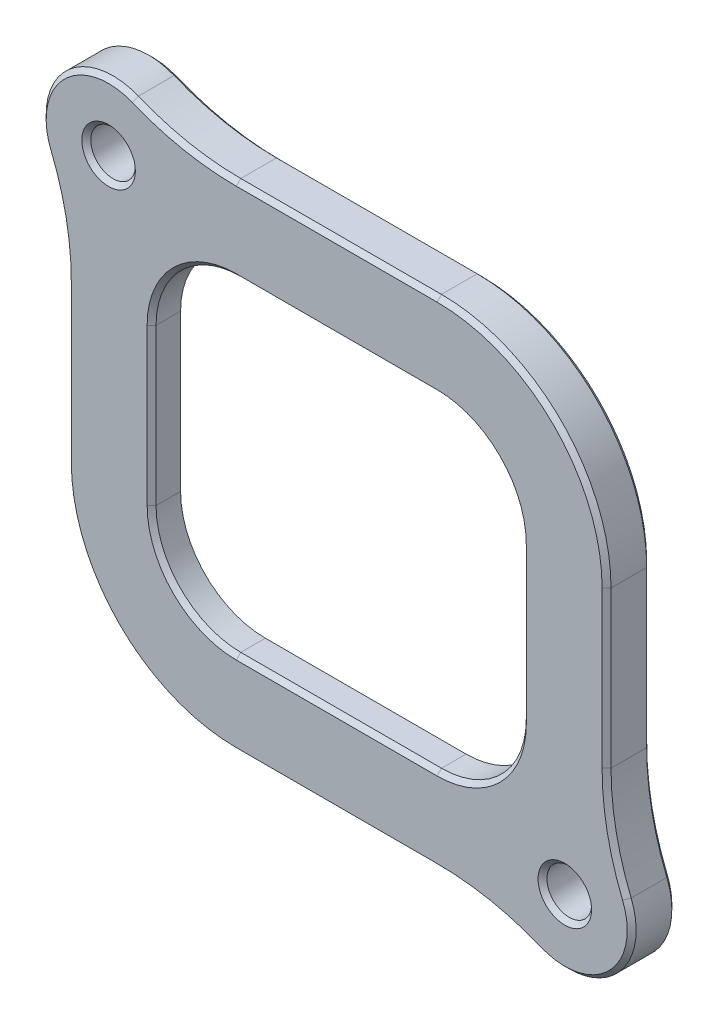
SolidWorks part; units mm, degrees
ref_plane "Ebene vorne" through (0, 0, 0) normal (1, 0, 0) x (0, 1, 0)
ref_plane "Ebene oben" through (0, 0, 0) normal (0, 0, 1) x (0, 1, 0)
ref_plane "Ebene rechts" through (0, 0, 0) normal (0, 1, 0) x (-1, 0, 0)
sketch "Skizze1" plane through (0, 0, 0) normal (0, 0, 1) x (0, 1, 0)
  line L0 (-3.5, 12.1) -> (3.5, 12.1)
  line L1 (-3.5, 9.5) -> (3.5, 9.5) construction
  line L2 (-8.5, 4.5) -> (-8.5, -4.5) construction
  line L3 (-3.5, -9.5) -> (3.5, -9.5) construction
  line L4 (8.5, 4.5) -> (8.5, -4.5) construction
  line L5 (-8.5, 9.5) -> (8.5, -9.5) construction
  line L6 (-8.5, -9.5) -> (8.5, 9.5) construction
  line L7 (11.1, 4.5) -> (11.1, -4.5)
  line L8 (-3.5, -12.1) -> (3.5, -12.1)
  line L9 (-11.1, 4.5) -> (-11.1, -4.5)
  line L10 (-3.5, 8.3) -> (3.5, 8.3)
  line L11 (7.3, 4.5) -> (7.3, -4.5)
  line L12 (-3.5, -8.3) -> (3.5, -8.3)
  line L13 (-7.3, 4.5) -> (-7.3, -4.5)
  line L14 (9.2276, 10.2276) -> (3.5, 4.5) construction
  line L15 (3.5, 4.5) -> (3.5, 12.1) construction
  line L16 (-3.5, -4.5) -> (-9.2276, -10.2276) construction
  line L17 (-3.5, -4.5) -> (-3.5, -12.1) construction
  line L18 (-3.5, 9.6) -> (3.5, 9.6) construction
  line L19 (8.6, 4.5) -> (8.6, -4.5) construction
  line L20 (-3.5, -9.6) -> (3.5, -9.6) construction
  line L21 (-8.6, 4.5) -> (-8.6, -4.5) construction
  line L22 (23.2106, 4.5) -> (11.1, 4.5) construction
  arc A0 (-3.5, 9.5) -> (-8.5, 4.5) centre (-3.5, 4.5) ccw construction
  arc A1 (-8.5, -4.5) -> (-3.5, -9.5) centre (-3.5, -4.5) ccw construction
  arc A2 (3.5, -9.5) -> (8.5, -4.5) centre (3.5, -4.5) ccw construction
  arc A3 (8.5, 4.5) -> (3.5, 9.5) centre (3.5, 4.5) ccw construction
  arc A5 (3.5, -12.1) -> (11.1, -4.5) centre (3.5, -4.5) ccw
  arc A7 (-3.5, 12.1) -> (-11.1, 4.5) centre (-3.5, 4.5) ccw
  arc A8 (7.3, 4.5) -> (3.5, 8.3) centre (3.5, 4.5) ccw
  arc A9 (3.5, -8.3) -> (7.3, -4.5) centre (3.5, -4.5) ccw
  arc A10 (-7.3, -4.5) -> (-3.5, -8.3) centre (-3.5, -4.5) ccw
  arc A11 (-3.5, 8.3) -> (-7.3, 4.5) centre (-3.5, 4.5) ccw
  arc A12 (7.1062, 8.1062) -> (7.185, 8.0303) centre (9.2276, 10.2276) ccw
  arc A13 (-12.0037, -9.0904) -> (-8.0904, -13.0037) centre (-9.2276, -10.2276) ccw
  arc A14 (8.6, 4.5) -> (3.5, 9.6) centre (3.5, 4.5) ccw construction
  arc A15 (3.5, -9.6) -> (8.6, -4.5) centre (3.5, -4.5) ccw construction
  arc A16 (-8.6, -4.5) -> (-3.5, -9.6) centre (-3.5, -4.5) ccw construction
  arc A17 (-3.5, 9.6) -> (-8.6, 4.5) centre (-3.5, 4.5) ccw construction
  arc A18 (12.0037, 9.0904) -> (11.1, 4.5) centre (23.2106, 4.5) ccw
  arc A19 (3.5, 12.1) -> (8.0904, 13.0037) centre (3.5, 24.2106) ccw
  arc A20 (-12.0037, -9.0904) -> (-11.1, -4.5) centre (-23.2106, -4.5) ccw
  arc A21 (-3.5, -12.1) -> (-8.0904, -13.0037) centre (-3.5, -24.2106) ccw
  arc A22 (12.0037, 9.0904) -> (8.0904, 13.0037) centre (9.2276, 10.2276) ccw
  arc A23 (11.1, 4.5) -> (3.5, 12.1) centre (3.5, 4.5) ccw construction
  arc A24 (-7.1062, -8.1062) -> (-7.185, -8.0303) centre (-9.2276, -10.2276) ccw
  arc A25 (-11.1, -4.5) -> (-3.5, -12.1) centre (-3.5, -4.5) ccw construction
  point P0 (0, 0)
  dimension "D3" = 5
  dimension "D8" = 6
  dimension "D1" = 17
  dimension "D2" = 19
  dimension "D6" = 45
  dimension "D7" = 45
  dimension "D4" = 2.6
  dimension "D5" = 1.2
  dimension "D9" = 0.1
extrude "Aufsatz-Linear austragen1" add sketch "Skizze1" along normal blind 2
hole_wizard "Ø2.0 (2) Durchmesser Bohrung1" positions "Skizze4" profile "Skizze3" hole size "Ø2.0" standard "DIN"
sketch "Skizze4" plane through (0, 0, 2) normal (0, 0, 1) x (0, -1, 0)
  arc A0 (-12.0037, -9.0904) -> (-8.0904, -13.0037) centre (-9.2276, -10.2276) ccw construction
  arc A1 (12.0037, 9.0904) -> (8.0904, 13.0037) centre (9.2276, 10.2276) ccw construction
  point P0 (-9.2276, -10.2276)
  point P3 (9.2276, 10.2276)
  point P7 (0, 0)
  point P11 (0, 0)
sketch "Skizze3" plane through (-10.2276, 9.2276, 2) normal (1, 0, 0) x (0, -1, 0)
  line L0 (0, 0) -> (0, 2.6009)
  line L1 (0, 2.6009) -> (1, 2)
  line L2 (1, 2) -> (1, 0)
  line L5 (1, 0) -> (0, 0)
  line L10 (0, 2.6009) -> (-1, 2) construction
  line L11 (0, -6.35) -> (0, 107.95) construction
  dimension "Bohrerdurchmesser" = 2
  dimension "Bohrungstiefe" = 2
  dimension "Spitzenwinkel" = 118
sketch "Skizze5" plane through (0, 0, 0) normal (0, 0, -1) x (1, 0, 0)
  line L1 (4.5, -8.6) -> (-4.5, -8.6)
  line L2 (9.6, -3.5) -> (9.6, 3.5)
  line L3 (4.5, 8.6) -> (-4.5, 8.6)
  line L4 (-9.6, -3.5) -> (-9.6, 3.5)
  line L5 (9.6, -8.6) -> (-9.6, 8.6) construction
  line L6 (9.6, 8.6) -> (-9.6, -8.6) construction
  arc A0 (-9.6, -3.5) -> (-4.5, -8.6) centre (-4.5, -3.5) ccw
  arc A1 (4.5, -8.6) -> (9.6, -3.5) centre (4.5, -3.5) ccw
  arc A2 (9.6, 3.5) -> (4.5, 8.6) centre (4.5, 3.5) ccw
  arc A3 (-4.5, 8.6) -> (-9.6, 3.5) centre (-4.5, 3.5) ccw
  point P0 (0, 0)
  dimension "D3" = 5.1
  dimension "D1" = 19.2
  dimension "D2" = 17.2
extrude "Schnitt-Linear austragen1" cut sketch "Skizze5" against normal blind 0.7
chamfer "Fase2" distance 0.2 angle 45 44 edges at (-12.3489, 11.3489, 0) (-12.3281, 5.8393, 0) (-12.1, 0, 0) (-9.874, -8.874, 0) (0, -11.1, 0) (6.8393, -11.3281, 0) (12.3489, -11.3489, 0) (12.3281, -5.8393, 0) (12.1, 0, 0) (9.874, 8.874, 0) (0, 11.1, 0) (-6.8393, 11.3281, 0) (0, 11.1, 2) (9.874, 8.874, 2) (12.1, 0, 2) (12.3281, -5.8393, 2) (12.3489, -11.3489, 2) (6.8393, -11.3281, 2) (0, -11.1, 2) (-9.874, -8.874, 2) (-12.1, 0, 2) (-12.3281, 5.8393, 2) (-12.3489, 11.3489, 2) (-6.8393, 11.3281, 2) (0, -7.3, 2) (7.187, -6.187, 2) (8.3, 0, 2) (7.187, 6.187, 2) (0, 7.3, 2) (-7.187, 6.187, 2) (-8.3, 0, 2) (-7.187, -6.187, 2) (11.2276, -9.2276, 2) (-9.2276, 9.2276, 2) (11.2276, -9.2276, 0) (-9.2276, 9.2276, 0) (8.1062, 7.1062, 0) (9.6, 0, 0) (8.1062, -7.1062, 0) (0, -8.6, 0) (-8.1062, -7.1062, 0) (-9.6, 0, 0) (-8.1062, 7.1062, 0) (0, 8.6, 0)
